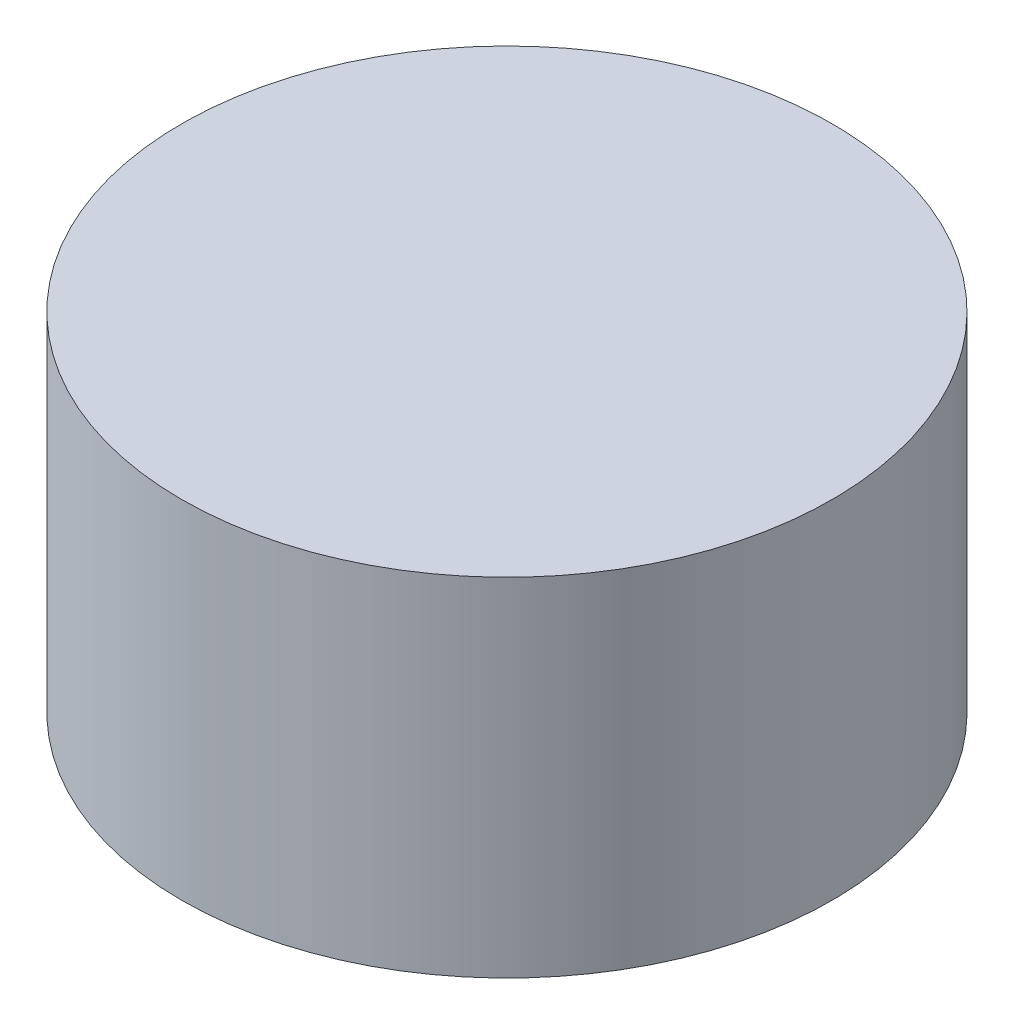
SolidWorks part; units mm, degrees
ref_plane "Front Plane" through (0, 0, 0) normal (0, 0, 1) x (1, 0, 0)
ref_plane "Top Plane" through (0, 0, 0) normal (0, 1, 0) x (1, 0, 0)
ref_plane "Right Plane" through (0, 0, 0) normal (1, 0, 0) x (0, 0, -1)
other "Configuration Table"
sketch "Sketch1" plane through (0, 0, 0) normal (0, 1, 0) x (1, 0, 0)
  circle A0 centre (0, 0) radius 61.4207
extrude "Boss-Extrude1" add sketch "Sketch1" along normal blind 65.532
